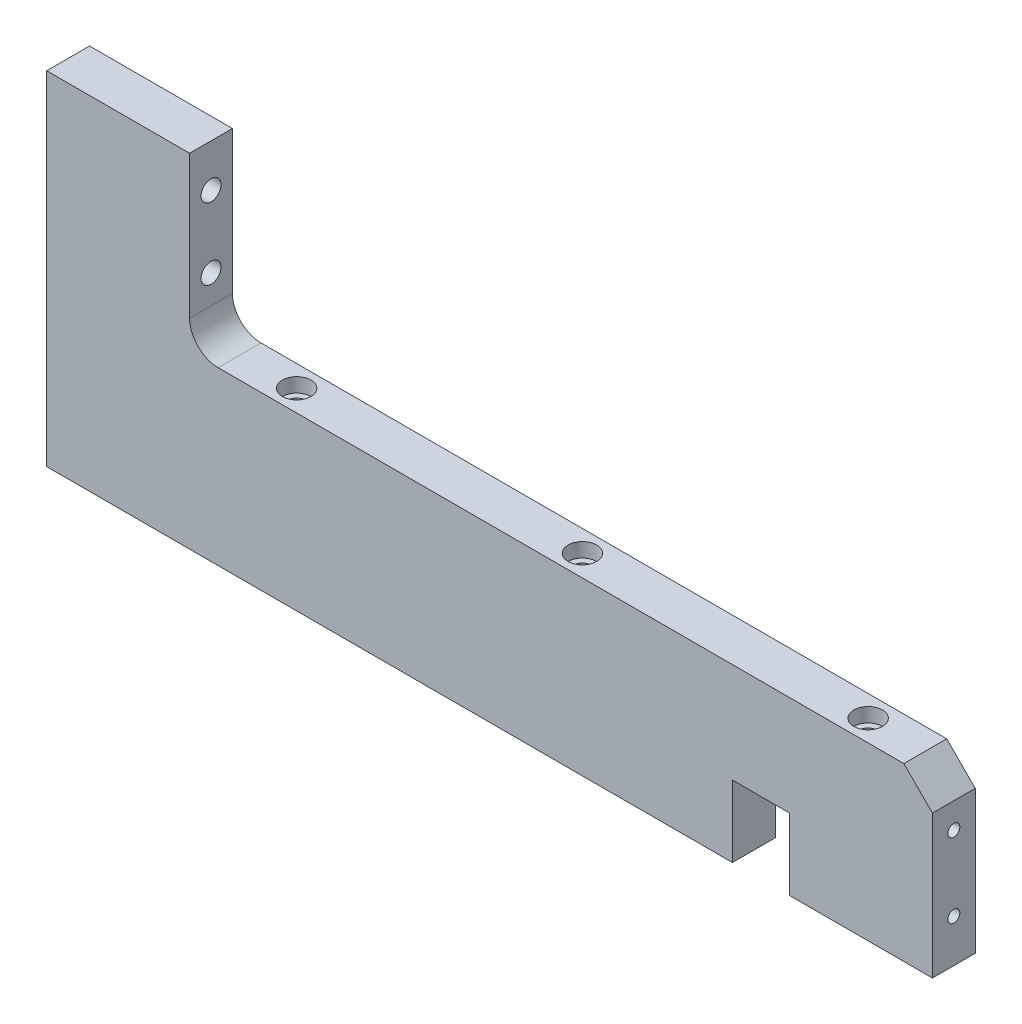
SolidWorks part; units mm, degrees
material "SKD11淬火HRC56-60"
ref_plane "前基準面" through (0, 0, 0) normal (0, 0, 1) x (1, 0, 0)
ref_plane "上基準面" through (0, 0, 0) normal (0, 1, 0) x (1, 0, 0)
ref_plane "右基準面" through (0, 0, 0) normal (1, 0, 0) x (0, 0, -1)
sketch "草图1" plane through (0, 0, 0) normal (0, 0, 1) x (1, 0, 0)
  line L1 (0, 0) -> (310, 0)
  line L2 (0, 0) -> (0, 120)
  line L3 (0, 120) -> (310, 120)
  line L4 (310, 0) -> (310, 120)
  dimension "D1" = 310
  dimension "D2" = 120
extrude "凸台-拉伸1" add sketch "草图1" along normal blind 15
sketch "草图2" plane through (0, 0, 15) normal (0, 0, 1) x (1, 0, 0)
  line L0 (310, 120) -> (0, 120) construction
  line L1 (310, 120) -> (50, 120)
  line L2 (310, 120) -> (310, 60)
  line L3 (310, 60) -> (50, 60)
  line L4 (50, 120) -> (50, 60)
  line L5 (0, 120) -> (0, 0) construction
  line L6 (310, 0) -> (310, 120) construction
  dimension "D2" = 50
  dimension "D3" = 60
extrude "切除-拉伸1" cut sketch "草图2" against normal through all
hole_wizard "M5 六角凹头螺钉的柱形沉头孔1" positions "草图4" profile "草图3" counterbore size "M5" standard "ISO" end condition through all
sketch "草图4" plane through (0, 60, 0) normal (0, 1, 0) x (-1, 0, 0)
  line L0 (-50, 7.5) -> (-310, 7.5) construction
  line L1 (-50, 0) -> (-50, 15) construction
  line L3 (-310, 0) -> (-310, 15) construction
  line L4 (-180, 0) -> (-180, 15) construction
  line L5 (-50, 0) -> (-310, 0) construction
  line L6 (-50, 15) -> (-310, 15) construction
  point P0 (-80, 7.5)
  point P16 (-280, 7.5)
  point P18 (-180, 7.5)
  dimension "D1" = 30
sketch "草图3" plane through (80, 60, 7.5) normal (1, 0, 0) x (0, 0, 1)
  line L0 (0, 0) -> (0, 60)
  line L1 (0, 60) -> (2.9, 60)
  line L3 (2.9, 60) -> (2.9, 5)
  line L4 (2.9, 5) -> (5, 5)
  line L5 (5, 5) -> (5, 0)
  line L7 (5, 0) -> (0, 0)
  line L11 (0, -6.35) -> (0, 107.95) construction
  dimension "通孔孔直径" = 5.8
  dimension "通孔孔深度" = 60
  dimension "柱形沉头孔直径" = 10
  dimension "柱形沉头孔深度" = 5
sketch "草图7" plane through (50, 0, 0) normal (1, 0, 0) x (0, 0, -1)
  line L0 (-7.5, 120) -> (-7.5, 60) construction
  line L1 (0, 120) -> (-15, 120) construction
  line L2 (0, 60) -> (-15, 60) construction
  circle A0 centre (-7.5, 80) radius 3.5
  circle A1 centre (-7.5, 105) radius 3.5
  dimension "D1" = 7
  dimension "D2" = 15
  dimension "D3" = 25
extrude "切除-拉伸2" cut sketch "草图7" against normal through all
chamfer "倒角1" distance 10 angle 45 1 edges at (310, 60, 7.5)
fillet "圆角1" radius 10 1 edges at (50, 60, 7.5)
hole_wizard "M5 螺纹孔1" positions "草图9" profile "草图8" tap size "M5" standard "ISO"
sketch "草图9" plane through (310, 0, 0) normal (1, 0, 0) x (0, 0, -1)
  line L0 (-7.5, 0) -> (-7.5, 50) construction
  line L1 (-15, 0) -> (0, 0) construction
  line L2 (0, 50) -> (-15, 50) construction
  point P0 (-7.5, 41)
  point P1 (-7.5, 15)
  dimension "D1" = 15
  dimension "D2" = 26
sketch "草图8" plane through (310, 41, 7.5) normal (0, 1, 0) x (0, 0, -1)
  line L0 (0, 0) -> (0, 13.6618)
  line L1 (0, 13.6618) -> (2.1, 12.4)
  line L2 (2.1, 12.4) -> (2.1, 0)
  line L5 (2.1, 0) -> (0, 0)
  line L10 (0, 13.6618) -> (-2.1, 12.4) construction
  line L11 (0, -6.35) -> (0, 107.95) construction
  dimension "螺纹孔钻头直径" = 4.2
  dimension "螺纹孔钻头深度" = 12.4
  dimension "导头角度" = 118
cosmetic thread "孔螺蚊线1" parameters "D1"=10, "D2"=5
cosmetic thread "孔螺蚊线2" parameters "D1"=10, "D2"=5
sketch "草图10" plane through (0, 0, 15) normal (0, 0, 1) x (1, 0, 0)
  line L0 (0, 0) -> (310, 0) construction
  line L1 (260, 25) -> (240, 25)
  line L2 (260, 25) -> (260, 0)
  line L3 (260, 0) -> (240, 0)
  line L4 (240, 25) -> (240, 0)
  line L7 (0, 120) -> (0, 0) construction
  dimension "D1" = 25
  dimension "D2" = 20
  dimension "D3" = 240
extrude "切除-拉伸3" cut sketch "草图10" against normal through all
